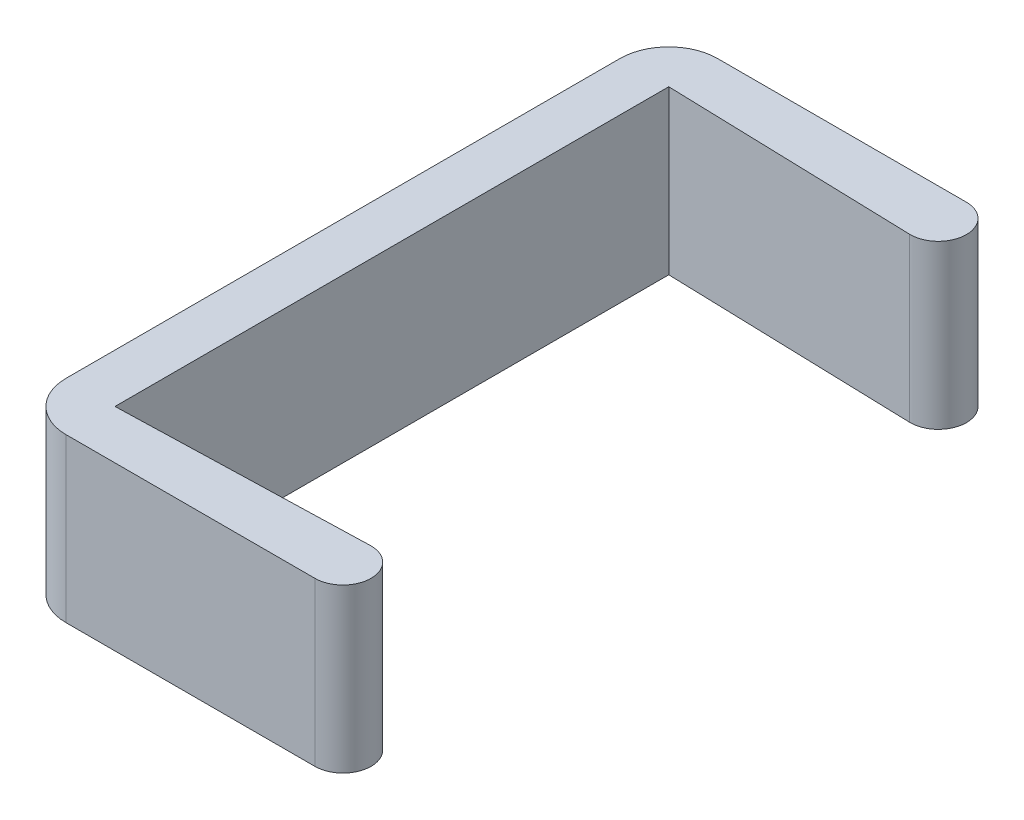
SolidWorks part; units mm, degrees
ref_plane "Front Plane" through (0, 0, 0) normal (0, 0, 1) x (1, 0, 0)
ref_plane "Top Plane" through (0, 0, 0) normal (0, 1, 0) x (1, 0, 0)
ref_plane "Right Plane" through (0, 0, 0) normal (1, 0, 0) x (0, 0, -1)
sketch "Sketch1" plane through (0, 0, 0) normal (0, 1, 0) x (1, 0, 0)
  line L0 (0, -16.5) -> (0, -20)
  line L1 (-20, 20) -> (0, 20)
  line L2 (-20, 20) -> (-20, -20)
  line L3 (-20, -20) -> (0, -20)
  line L4 (0, 20) -> (0, 16.5)
  line L5 (-17, 17) -> (0, 16.5)
  line L6 (-17, 17) -> (-17, -17)
  line L7 (-17, -17) -> (0, -16.5)
  line L8 (0, 16.5) -> (0, -16.5) construction
  point P10 (-20, 0)
  point P11 (-17, 0)
  dimension "D1" = 34
  dimension "D2" = 3
  dimension "D4" = 33
  dimension "D5" = 20
  dimension "D6" = 3
extrude "Boss-Extrude1" add sketch "Sketch1" along normal blind 10
fillet "Fillet1" radius 3 2 edges at (-20, 5, -20) (-20, 5, 20)
fillet "Fillet2" radius 1.7243 4 edges at (0, 0, 18.25) (0, 10, 18.25) (0, 5, 16.5) (0, 5, 20)
fillet "Fillet3" radius 1.7243 4 edges at (0, 5, -20) (0, 5, -16.5) (0, 10, -18.25) (0, 0, -18.25)
